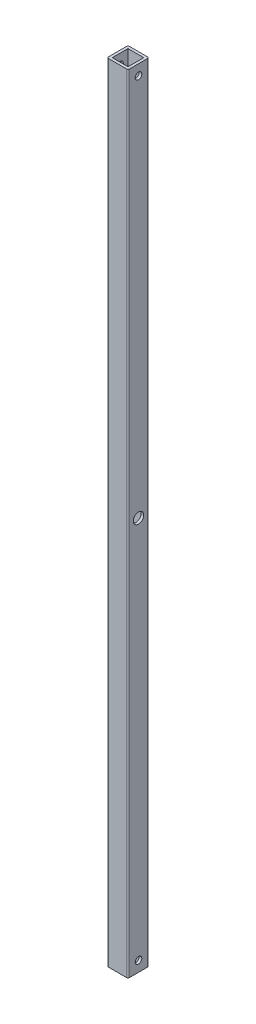
SolidWorks part; units mm, degrees
ref_plane "Front Plane" through (0, 0, 0) normal (0, 0, 1) x (1, 0, 0)
ref_plane "Top Plane" through (0, 0, 0) normal (0, 1, 0) x (1, 0, 0)
ref_plane "Right Plane" through (0, 0, 0) normal (1, 0, 0) x (0, 0, -1)
sketch "Sketch1" plane through (0, 0, 0) normal (0, 1, 0) x (1, 0, 0)
  line L0 (-6.3437, 2.7188) -> (-6.3437, -9.2812)
  line L1 (-8.3437, 4.7188) -> (7.6563, 4.7188)
  line L2 (-8.3437, 4.7188) -> (-8.3437, -11.2812)
  line L3 (-8.3437, -11.2812) -> (7.6563, -11.2812)
  line L4 (7.6563, 4.7188) -> (7.6563, -11.2812)
  line L5 (-6.3437, -9.2812) -> (5.6563, -9.2812)
  line L6 (5.6563, 2.7188) -> (5.6563, -9.2812)
  line L7 (-6.3437, 2.7188) -> (5.6563, 2.7188)
  dimension "D1" = 16
  dimension "D2" = 16
  dimension "D3" = 2
extrude "Boss-Extrude1" add sketch "Sketch1" along normal blind 600
fillet "Fillet1" radius 1 4 edges at (7.6563, 300, -4.7188) (-8.3437, 300, -4.7188) (-8.3437, 300, 11.2812) (7.6563, 300, 11.2812)
sketch "Sketch2" plane through (-8.3437, 0, 0) normal (-1, 0, 0) x (0, 0, 1)
  line L0 (-4.7188, 0) -> (-4.7188, 600) construction
  line L1 (-3.7188, 0) -> (10.2812, 0) construction
  circle A0 centre (3.2812, 300) radius 4
  dimension "D1" = 8
  dimension "D2" = 8
  dimension "D3" = 300
extrude "Cut-Extrude1" cut sketch "Sketch2" against normal blind 16
sketch "Sketch6" plane through (-8.3437, 0, 0) normal (-1, 0, 0) x (0, 0, 1)
  line L0 (-3.7188, 0) -> (10.2812, 0) construction
  line L1 (-4.7188, 0) -> (-4.7188, 600) construction
  line L2 (-3.7188, 600) -> (10.2812, 600) construction
  line L3 (-4.7188, 0) -> (-4.7188, 600) construction
  circle A0 centre (3.2812, 8) radius 2.5
  circle A1 centre (3.2812, 592) radius 2.5
  dimension "D1" = 5
  dimension "D4" = 5
  dimension "D2" = 8
  dimension "D3" = 8
  dimension "D5" = 8
  dimension "D6" = 8
extrude "Cut-Extrude3" cut sketch "Sketch6" against normal blind 20
